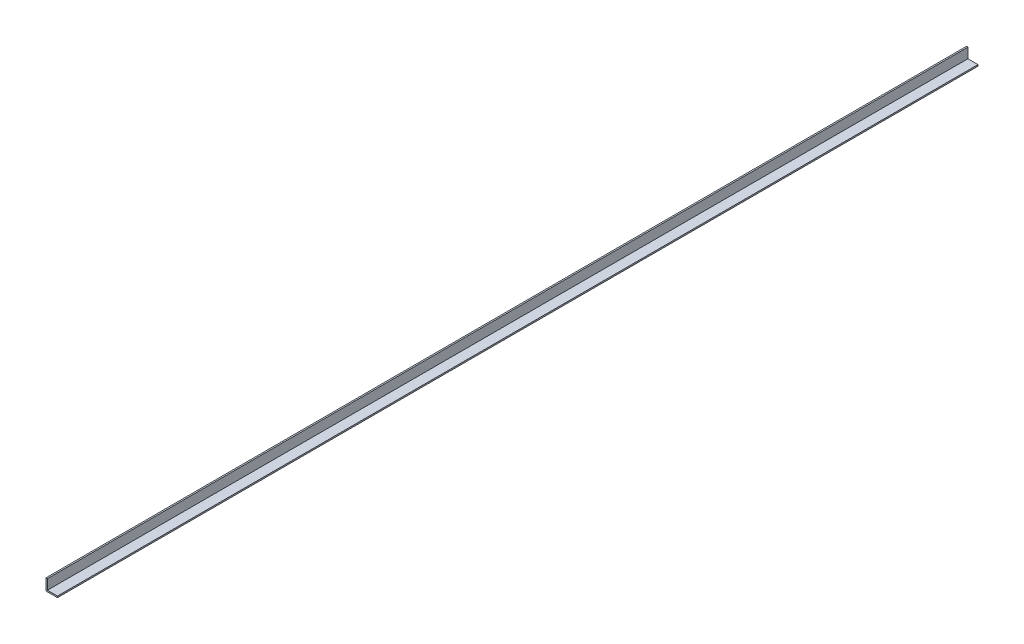
SolidWorks part; units mm, degrees
material "ASTM A36 Acero"
ref_plane "Alzado" through (0, 0, 0) normal (0, 0, 1) x (1, 0, 0)
ref_plane "Planta" through (0, 0, 0) normal (0, 1, 0) x (1, 0, 0)
ref_plane "Vista lateral" through (0, 0, 0) normal (1, 0, 0) x (0, 0, -1)
sketch "Croquis1" plane through (0, 0, 0) normal (0, 0, 1) x (1, 0, 0)
  line L0 (0, 76.2) -> (0, 0)
  line L1 (0, 0) -> (76.2, 0)
  line L2 (76.2, 0) -> (76.2, 9.53)
  line L3 (76.2, 9.53) -> (9.53, 9.53)
  line L4 (9.53, 9.53) -> (9.53, 76.2)
  line L5 (9.53, 76.2) -> (0, 76.2)
  dimension "D1" = 9.53
  dimension "D2" = 76.2
extrude "Saliente-Extruir1" add sketch "Croquis1" against normal blind 6100
